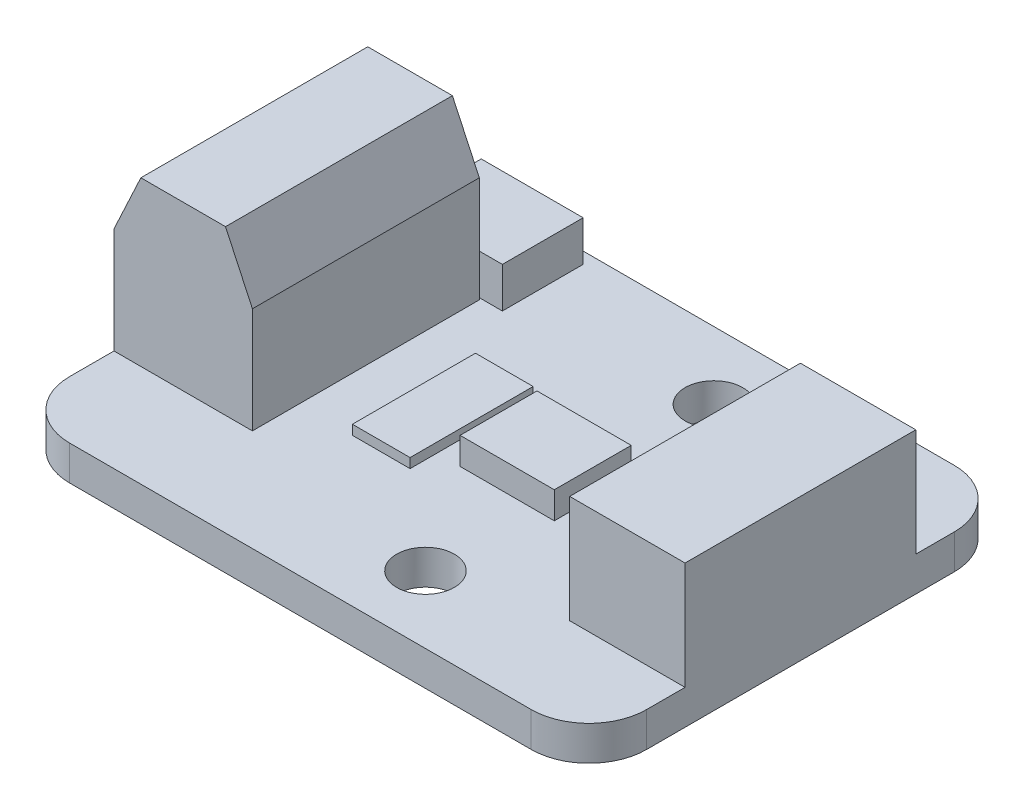
SolidWorks part; units mm, degrees
ref_plane "Front Plane" through (0, 0, 0) normal (0, 0, 1) x (1, 0, 0)
ref_plane "Top Plane" through (0, 0, 0) normal (0, 1, 0) x (1, 0, 0)
ref_plane "Right Plane" through (0, 0, 0) normal (1, 0, 0) x (0, 0, -1)
sketch "Sketch1" plane through (0, 0, 0) normal (0, 1, 0) x (1, 0, 0)
  line L1 (0, 0) -> (30, 0)
  line L2 (0, 0) -> (0, 22)
  line L3 (0, 22) -> (30, 22)
  line L4 (30, 0) -> (30, 22)
  dimension "D1" = 22
  dimension "D2" = 30
extrude "Boss-Extrude1" add sketch "Sketch1" along normal blind 1.8
sketch "Sketch2" plane through (0, 1.8, 0) normal (0, 1, 0) x (1, 0, 0)
  line L0 (0, 0) -> (30, 0) construction
  line L1 (30, 22) -> (0, 22) construction
  line L3 (30, 0) -> (30, 22) construction
  circle A0 centre (18, 18.5) radius 1.5
  circle A1 centre (18, 3.5) radius 1.5
  point P4 (12.8684, 8.2445)
  point P9 (0, 0)
  dimension "D1" = 3
  dimension "D2" = 3
  dimension "D3" = 3.5
  dimension "D4" = 3.5
  dimension "D5" = 12
extrude "Cut-Extrude1" cut sketch "Sketch2" against normal up to surface (1.8 mm away) up to face at (15, 0, -11)
sketch "Sketch3" plane through (0, 1.8, 0) normal (0, 1, 0) x (1, 0, 0)
  line L0 (0, 0) -> (30, 0) construction
  line L1 (0, 17.1) -> (7.2, 17.1)
  line L2 (0, 17.1) -> (0, 5.3)
  line L3 (0, 5.3) -> (7.2, 5.3)
  line L4 (7.2, 17.1) -> (7.2, 5.3)
  line L5 (0, 22) -> (0, 0) construction
  dimension "D1" = 7.2
  dimension "D2" = 11.8
  dimension "D3" = 5.3
extrude "Boss-Extrude2" add sketch "Sketch3" along normal blind 8.5
sketch "Sketch4" plane through (0, 1.8, 0) normal (0, 1, 0) x (1, 0, 0)
  line L0 (0, 0) -> (30, 0) construction
  line L1 (24, 17) -> (30, 17)
  line L2 (24, 17) -> (24, 5)
  line L3 (24, 5) -> (30, 5)
  line L4 (30, 17) -> (30, 5)
  line L5 (30, 0) -> (30, 22) construction
  dimension "D1" = 6
  dimension "D2" = 12
  dimension "D3" = 5
extrude "Boss-Extrude3" add sketch "Sketch4" along normal blind 5.6
sketch "Sketch5" plane through (0, 1.8, 0) normal (0, 1, 0) x (1, 0, 0)
  line L0 (0, 22) -> (0, 17.1) construction
  line L1 (3, 21.4) -> (8.3, 21.4)
  line L2 (3, 21.4) -> (3, 17.2)
  line L3 (3, 17.2) -> (8.3, 17.2)
  line L4 (8.3, 21.4) -> (8.3, 17.2)
  line L5 (30, 22) -> (0, 22) construction
  dimension "D1" = 5.3
  dimension "D2" = 4.2
  dimension "D3" = 3
  dimension "D4" = 0.6
extrude "Boss-Extrude4" add sketch "Sketch5" along normal blind 2.1
sketch "Sketch6" plane through (0, 1.8, 0) normal (0, 1, 0) x (1, 0, 0)
  line L0 (24, 17) -> (24, 5) construction
  line L1 (14.2, 13.1) -> (19.1, 13.1)
  line L2 (14.2, 13.1) -> (14.2, 9.1)
  line L3 (14.2, 9.1) -> (19.1, 9.1)
  line L4 (19.1, 13.1) -> (19.1, 9.1)
  line L5 (0, 0) -> (30, 0) construction
  dimension "D1" = 4
  dimension "D2" = 4.9
  dimension "D3" = 4.9
  dimension "D4" = 9.1
extrude "Boss-Extrude5" add sketch "Sketch6" along normal blind 1.4
sketch "Sketch7" plane through (0, 1.8, 0) normal (0, 1, 0) x (1, 0, 0)
  line L0 (0, 0) -> (30, 0) construction
  line L1 (10, 14.1) -> (13, 14.1)
  line L2 (10, 14.1) -> (10, 7.7)
  line L3 (10, 7.7) -> (13, 7.7)
  line L4 (13, 14.1) -> (13, 7.7)
  line L5 (14.2, 13.1) -> (14.2, 9.1) construction
  dimension "D1" = 3
  dimension "D2" = 6.4
  dimension "D3" = 7.7
  dimension "D4" = 1.2
extrude "Boss-Extrude6" add sketch "Sketch7" along normal blind 0.5
fillet "Fillet1" radius 3 4 edges at (0, 0.9, -22) (30, 0.9, -22) (30, 0.9, 0) (0, 0.9, 0)
chamfer "Chamfer1" distance 3 angle 25 2 edges at (7.2, 10.3, -11.2) (0, 10.3, -11.2)
